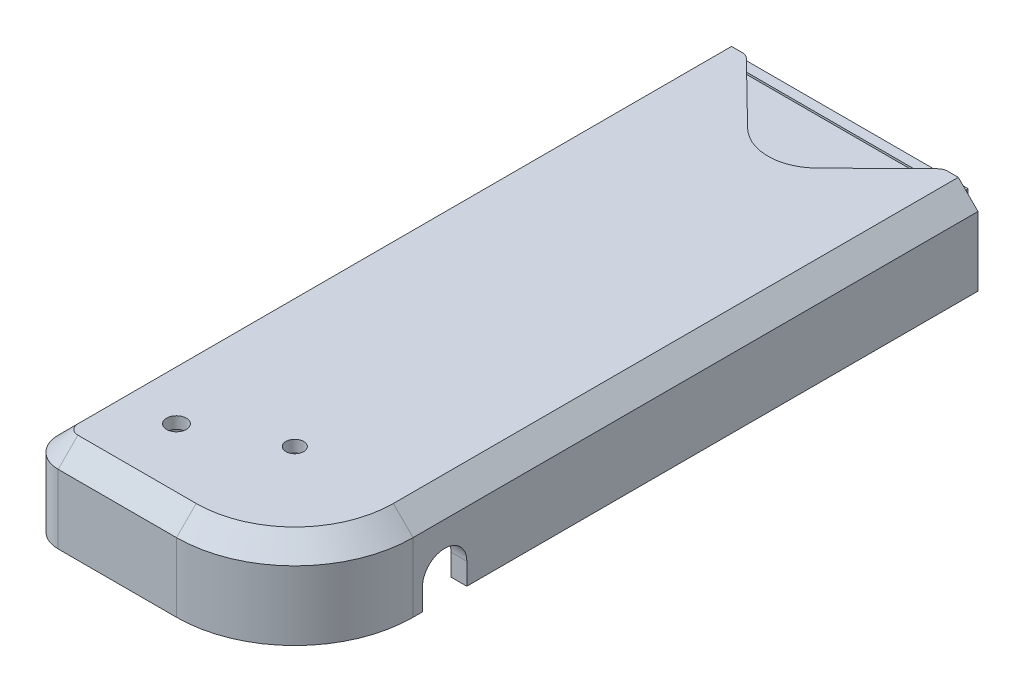
SolidWorks part; units mm, degrees
ref_plane "Спереди" through (0, 0, 0) normal (0, 0, 1) x (1, 0, 0)
ref_plane "Сверху" through (0, 0, 0) normal (0, 1, 0) x (1, 0, 0)
ref_plane "Справа" through (0, 0, 0) normal (1, 0, 0) x (0, 0, -1)
sketch "Эскиз1" plane through (0, 0, 0) normal (0, 1, 0) x (1, 0, 0)
  line L1 (-13.5, 35.6) -> (13.5, 35.6)
  line L2 (-13.5, 35.6) -> (-13.5, -32.6)
  line L3 (-10.5, -35.6) -> (1.5, -35.6)
  line L4 (13.5, 35.6) -> (13.5, -23.6)
  line L5 (-13.5, 35.6) -> (13.5, -35.6) construction
  line L6 (-13.5, -35.6) -> (13.5, 35.6) construction
  arc A0 (13.5, -23.6) -> (1.5, -35.6) centre (1.5, -23.6) cw
  arc A1 (-10.5, -35.6) -> (-13.5, -32.6) centre (-10.5, -32.6) cw
  point P0 (0, 0)
  dimension "D3" = 12
  dimension "D4" = 3
  dimension "D1" = 27
  dimension "D2" = 71.2
extrude "Бобышка-Вытянуть1" add sketch "Эскиз1" along normal blind 9
sketch "Эскиз2" plane through (0, 0, -35.6) normal (0, 0, -1) x (-1, 0, 0)
  line L1 (7.05, -6) -> (-7.05, -6)
  line L2 (7.05, -6) -> (7.05, 6)
  line L3 (7.05, 6) -> (-7.05, 6)
  line L4 (-7.05, -6) -> (-7.05, 6)
  line L5 (7.05, -6) -> (-7.05, 6) construction
  line L6 (7.05, 6) -> (-7.05, -6) construction
  line L7 (-13.5, 0) -> (13.5, 0) construction
  line L8 (6.05, 5) -> (-6.05, 5)
  line L9 (-6.05, -5) -> (-6.05, 5)
  line L10 (6.05, -5) -> (-6.05, -5)
  line L11 (6.05, -5) -> (6.05, 5)
  circle A0 centre (0, 0) radius 27.0858
  line M6 (-13.5, 0) -> (13.5, 0)
  line M7 (13.5, 0) -> (13.5, 9)
  line M8 (13.5, 9) -> (-13.5, 9)
  line M9 (-13.5, 9) -> (-13.5, 0)
  dimension "D1" = 14.1
  dimension "D2" = 6
  dimension "D3" = 1
extrude "Вырез-Вытянуть1" cut sketch "Эскиз2" against normal blind 0.9 contours L4 L3 L2 M6 M7 M8 M9 | L11 L8 L9 M6
sketch "Эскиз3" plane through (0, 0, -34.7) normal (0, 0, -1) x (-1, 0, 0)
  line L1 (11.5, -7.5) -> (-11.5, -7.5)
  line L2 (11.5, -7.5) -> (11.5, 7.5)
  line L3 (11.5, 7.5) -> (-11.5, 7.5)
  line L4 (-11.5, -7.5) -> (-11.5, 7.5)
  line L5 (11.5, -7.5) -> (-11.5, 7.5) construction
  line L6 (11.5, 7.5) -> (-11.5, -7.5) construction
  line L7 (-13.5, 0) -> (-7.05, 0) construction
  line L8 (-6.05, 0) -> (6.05, 0) construction
  circle A0 centre (0, 0) radius 29.4019
  dimension "D1" = 23
  dimension "D2" = 7.5
extrude "Вырез-Вытянуть2" cut sketch "Эскиз3" against normal blind 1
chamfer "Фаска1" distance 2 angle 45 5 edges at (13.5, 9, -5.05) (9.9853, 9, 32.0853) (-4.5, 9, 35.6) (-12.6213, 9, 34.7213) (-13.5, 9, -0.55)
sketch "Эскиз4" plane through (0, 0, 0) normal (0, -1, 0) x (1, 0, 0)
  line L32 (9.9, -33.1) -> (9.9, -32.1)
  line L33 (9.9, -32.1) -> (11.9, -32.1)
  line L34 (11.9, -32.1) -> (11.9, 23.6)
  line L35 (1.5, 34) -> (-10.5, 34)
  line L36 (-11.9, 32.6) -> (-11.9, -32.1)
  line L37 (-11.9, -32.1) -> (-9.9, -32.1)
  line L38 (-9.9, -32.1) -> (-9.9, -33.1)
  line L39 (-9.9, -33.1) -> (9.9, -33.1)
  line L40 (9.9, -33.1) -> (9.9, -32.1)
  line L41 (9.9, -32.1) -> (11.9, -32.1)
  line L42 (11.9, -32.1) -> (11.9, 23.6)
  line L43 (1.5, 34) -> (-10.5, 34)
  line L44 (-11.9, 32.6) -> (-11.9, -32.1)
  line L45 (-11.9, -32.1) -> (-9.9, -32.1)
  line L46 (-9.9, -32.1) -> (-9.9, -33.1)
  line L47 (-9.9, -33.1) -> (9.9, -33.1)
  arc A4 (11.9, 23.6) -> (1.5, 34) centre (1.5, 23.6) ccw
  arc A5 (-10.5, 34) -> (-11.9, 32.6) centre (-10.5, 32.6) ccw
  arc A6 (11.9, 23.6) -> (1.5, 34) centre (1.5, 23.6) ccw
  arc A7 (-10.5, 34) -> (-11.9, 32.6) centre (-10.5, 32.6) ccw
  dimension "D1" = 1.6
extrude "Вырез-Вытянуть4" cut sketch "Эскиз4" against normal blind 7.8
sketch "Эскиз5" plane through (0, 0, 0) normal (0, -1, 0) x (1, 0, 0)
  line L0 (-9.9, -33.1) -> (9.9, -33.1) construction
  line L1 (6.05, -34.7) -> (-6.05, -34.7)
  line L2 (6.05, -34.7) -> (6.05, -33.1)
  line L3 (6.05, -33.1) -> (-6.05, -33.1)
  line L4 (-6.05, -34.7) -> (-6.05, -33.1)
extrude "Вырез-Вытянуть5" cut sketch "Эскиз5" against normal up to surface (5 mm away) up to face at (0, 5, -35.15)
sketch "Эскиз6" plane through (0, 9, 0) normal (0, 1, 0) x (1, 0, 0)
  line L0 (-13.5, -32.6) -> (-13.5, 33.7) construction
  line L1 (1.5, -35.6) -> (-10.5, -35.6) construction
  circle A0 centre (-6.5, -27.6) radius 1
  circle A1 centre (1.5, -23.6) radius 0.9
  arc A2 (1.5, -35.6) -> (13.5, -23.6) centre (1.5, -23.6) ccw construction
  dimension "D3" = 2
  dimension "D4" = 1.8
  dimension "D1" = 7
  dimension "D2" = 8
extrude "Вырез-Вытянуть6" cut sketch "Эскиз6" against normal blind 3
sketch "Эскиз8" plane through (13.5, 0, 0) normal (1, 0, 0) x (0, 0, -1)
  line L0 (-22.65, 2.2) -> (-22.65, 0)
  line L1 (-23.6, 0) -> (33.7, 0) construction
  line L2 (-18.15, 2.2) -> (-18.15, 0)
  line L3 (-22.65, 0) -> (-18.15, 0)
  circle A0 centre (-20.4, 2.2) radius 2.25 construction
  arc A1 (-18.15, 2.2) -> (-22.65, 2.2) centre (-20.4, 2.2) ccw
extrude "Вырез-Вытянуть7" cut sketch "Эскиз8" against normal blind 3
sketch "Эскиз9" plane through (0, 9, 0) normal (0, 1, 0) x (1, 0, 0)
  line L0 (0, 33.7) -> (0, 30.9002) construction
  line L1 (-11.5, 33.7) -> (11.5, 33.7) construction
  line L2 (-10, 33.7) -> (-3.5, 27.3292)
  line L3 (-11.5, 33.7) -> (11.5, 33.7) construction
  line L4 (10, 33.7) -> (3.5, 27.3292)
  line L5 (-10, 33.7) -> (10, 33.7)
  arc A0 (-3.5, 27.3292) -> (3.5, 27.3292) centre (0, 30.9002) ccw
  dimension "D1" = 10
  dimension "D2" = 10
  dimension "D3" = 7.8
  dimension "D4" = 7
sketch "Эскиз10" plane through (0, 9, 0) normal (0, 1, 0) x (1, 0, 0)
  line L4 (-11.5, 33.7) -> (11.5, 33.7)
  line L5 (-11.5, 33.7) -> (-11.5, -32.6) construction
  line L8 (4.62, 26.1865) -> (11.5, 33.7)
  line L9 (-11.5, 33.7) -> (-4.62, 26.1865)
  line L10 (-11.5, 33.7) -> (11.5, 33.7) construction
  arc A4 (-4.62, 26.1865) -> (4.62, 26.1865) centre (0, 30.9002) ccw
extrude "Бобышка-Вытянуть2" add sketch "Эскиз10" against normal blind 3
extrude "Вырез-Вытянуть9" cut sketch "Эскиз9" against normal blind 1.7
fillet "Скругление1" radius 1 2 edges at (10, 8.25, -33.7) (-10, 8.25, -33.7)
